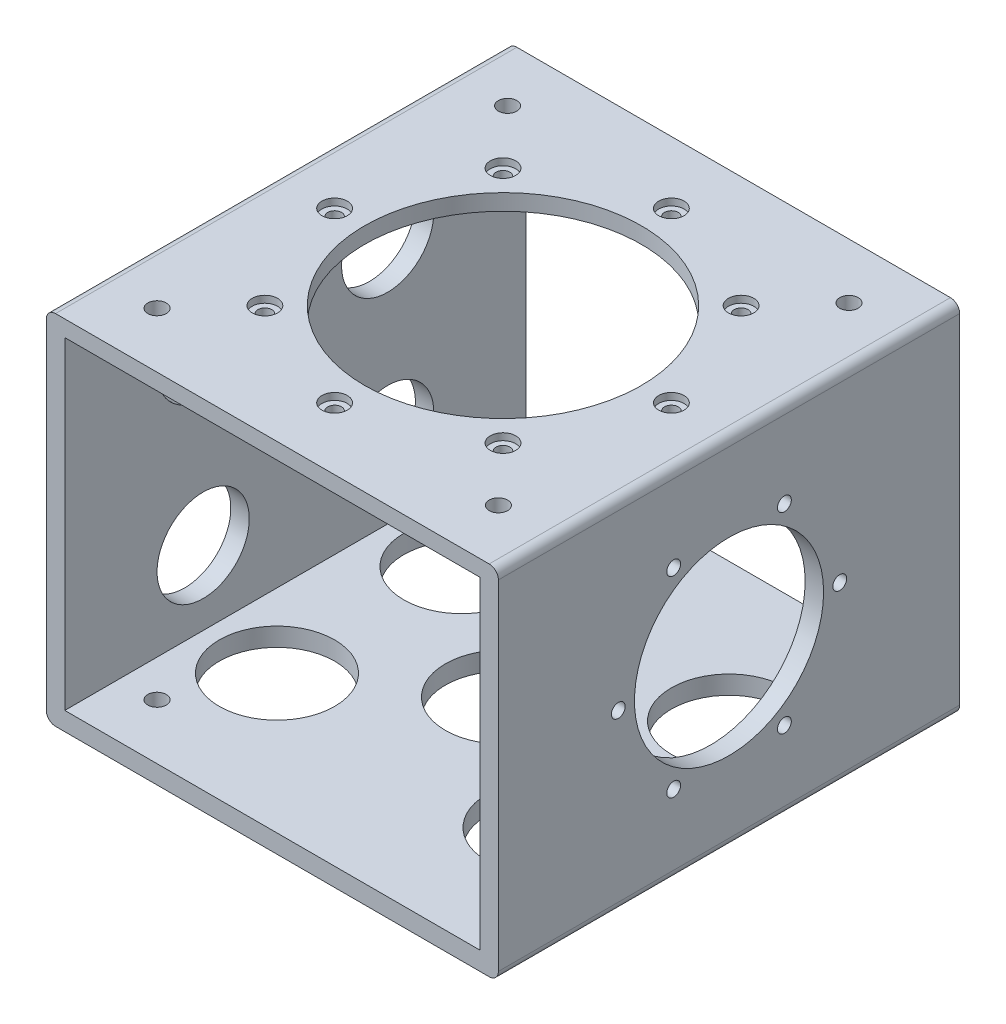
SolidWorks part; units mm, degrees
ref_plane "前视基准面" through (0, 0, 0) normal (0, 0, 1) x (1, 0, 0)
ref_plane "上视基准面" through (0, 0, 0) normal (0, 1, 0) x (1, 0, 0)
ref_plane "右视基准面" through (0, 0, 0) normal (1, 0, 0) x (0, 0, -1)
sketch "草图1" plane through (0, 0, 0) normal (0, 1, 0) x (1, 0, 0)
  line L1 (-45, 40) -> (45, 40)
  line L2 (-45, 40) -> (-45, -40)
  line L3 (-45, -40) -> (45, -40)
  line L4 (45, 40) -> (45, -40)
  line L5 (-45, 40) -> (45, -40) construction
  line L6 (-45, -40) -> (45, 40) construction
  circle A0 centre (0, 0) radius 30
  point P0 (0, 0)
  dimension "D3" = 60
  dimension "D1" = 80
  dimension "D2" = 90
extrude "凸台-拉伸1" add sketch "草图1" along normal blind 4
sketch "草图2" plane through (0, 4, 0) normal (0, 1, 0) x (1, 0, 0)
  circle A0 centre (0, 0) radius 36.5 construction
  circle A1 centre (0, 36.5) radius 1.5
  circle A2 centre (25.8094, 25.8094) radius 1.5
  circle A3 centre (36.5, 0) radius 1.5
  circle A4 centre (25.8094, -25.8094) radius 1.5
  circle A5 centre (0, -36.5) radius 1.5
  circle A6 centre (-25.8094, -25.8094) radius 1.5
  circle A7 centre (-36.5, 0) radius 1.5
  circle A8 centre (-25.8094, 25.8094) radius 1.5
  point P22 (0, 0)
  dimension "D1" = 73
  dimension "D2" = 3
  dimension "D3" = 8
extrude "切除-拉伸1" cut sketch "草图2" against normal blind 4
sketch "草图3" plane through (45, 0, 0) normal (1, 0, 0) x (0, 0, -1)
  line L1 (-40, 4) -> (40, 4)
  line L2 (-40, 4) -> (-40, -76)
  line L3 (-40, -76) -> (40, -76)
  line L4 (40, 4) -> (40, -76)
  dimension "D1" = 80
extrude "凸台-拉伸2" add sketch "草图3" along normal blind 4
sketch "草图4" plane through (-45, 0, 0) normal (-1, 0, 0) x (0, 0, 1)
  line L4 (40, -76) -> (40, 4)
  line L5 (-40, -76) -> (40, -76)
  line L6 (-40, 4) -> (-40, -76)
  line L7 (40, 4) -> (-40, 4)
  line L8 (40, -76) -> (40, 4)
  line L9 (-40, -76) -> (40, -76)
  line L10 (-40, 4) -> (-40, -76)
  line L11 (40, 4) -> (-40, 4)
  dimension "D1" = 0
extrude "凸台-拉伸3" add sketch "草图4" along normal blind 4
sketch "草图5" plane through (49, 0, 0) normal (1, 0, 0) x (0, 0, -1)
  line L0 (-40, -76) -> (40, -76) construction
  circle A0 centre (0, -36) radius 40 construction
  circle A1 centre (0, -36) radius 24 construction
  circle A2 centre (-24, -36) radius 1.5
  circle A3 centre (-12, -15.2154) radius 1.5
  circle A4 centre (12, -15.2154) radius 1.5
  circle A5 centre (24, -36) radius 1.5
  circle A6 centre (12, -56.7846) radius 1.5
  circle A7 centre (-12, -56.7846) radius 1.5
  point P20 (0, -36)
  dimension "D2" = 80
  dimension "D3" = 48
  dimension "D4" = 3
  dimension "D1" = 40
  dimension "D5" = 6
extrude "切除-拉伸2" cut sketch "草图5" against normal blind 4
sketch "草图6" plane through (49, 0, 0) normal (1, 0, 0) x (0, 0, -1)
  line L0 (-40, -76) -> (40, -76) construction
  circle A0 centre (0, -36) radius 20.5
  dimension "D2" = 41
  dimension "D1" = 40
extrude "切除-拉伸3" cut sketch "草图6" against normal blind 4
sketch "草图8" plane through (0, -76, 0) normal (0, -1, 0) x (1, 0, 0)
  line L1 (-49, 40) -> (49, 40)
  line L2 (-49, 40) -> (-49, -40)
  line L3 (-49, -40) -> (49, -40)
  line L4 (49, 40) -> (49, -40)
extrude "凸台-拉伸4" add sketch "草图8" against normal blind 4
sketch "草图9" plane through (-49, 0, 0) normal (-1, 0, 0) x (0, 0, 1)
  line L0 (0, 0) -> (0, -70.3657) construction
  line L1 (-46.4501, -36) -> (45.1919, -36) construction
  circle A0 centre (0, -36) radius 8
  dimension "D1" = 16
extrude "切除-拉伸5" cut sketch "草图9" against normal blind 4
sketch "草图10" plane through (0, 4, 0) normal (0, 1, 0) x (1, 0, 0)
  circle A0 centre (-25.8094, 25.8094) radius 2.75
  circle A1 centre (0, 36.5) radius 2.75
  circle A2 centre (25.8094, 25.8094) radius 2.75
  circle A3 centre (36.5, 0) radius 2.75
  circle A4 centre (25.8094, -25.8094) radius 2.75
  circle A5 centre (0, -36.5) radius 2.75
  circle A6 centre (-25.8094, -25.8094) radius 2.75
  circle A7 centre (-36.5, 0) radius 2.75
  point P20 (0, 0)
  dimension "D1" = 5.5
  dimension "D2" = 8
extrude "切除-拉伸6" cut sketch "草图10" against normal blind 2
sketch "草图11" plane through (0, -76, 0) normal (0, -1, 0) x (1, 0, 0)
  line L1 (-52.2176, 44.2603) -> (53.8702, 44.2603)
  line L2 (-52.2176, 44.2603) -> (-52.2176, -42.4352)
  line L3 (-52.2176, -42.4352) -> (53.8702, -42.4352)
  line L4 (53.8702, 44.2603) -> (53.8702, -42.4352)
extrude "切除-拉伸7" cut sketch "草图11" against normal blind 2
sketch "草图12" plane through (0, -72, 0) normal (0, 1, 0) x (1, 0, 0)
  line L4 (-45, -40) -> (45, -40)
  line L5 (45, -40) -> (45, 40)
  line L6 (45, 40) -> (-45, 40)
  line L7 (-45, 40) -> (-45, -40)
  line L8 (-45, -40) -> (45, -40)
  line L9 (45, -40) -> (45, 40)
  line L10 (45, 40) -> (-45, 40)
  line L11 (-45, 40) -> (-45, -40)
  dimension "D1" = 0
extrude "凸台-拉伸5" add sketch "草图12" along normal blind 2
sketch "草图13" plane through (0, 4, 0) normal (0, 1, 0) x (1, 0, 0)
  line L1 (-60.0477, 50.6634) -> (55.7544, 50.6634)
  line L2 (-60.0477, 50.6634) -> (-60.0477, -44.4127)
  line L3 (-60.0477, -44.4127) -> (55.7544, -44.4127)
  line L4 (55.7544, 50.6634) -> (55.7544, -44.4127)
extrude "切除-拉伸8" cut sketch "草图13" against normal blind 0.5
sketch "草图14" plane through (0, -74, 0) normal (0, -1, 0) x (1, 0, 0)
  line L0 (-49, -40) -> (-49, 40) construction
  line L1 (49, 40) -> (-49, 40) construction
  line L2 (49, 40) -> (49, -40) construction
  line L3 (-49, -40) -> (49, -40) construction
  circle A0 centre (-29, 20) radius 12.5
  circle A1 centre (29, 20) radius 12.5
  circle A2 centre (0, 0) radius 12.5
  circle A3 centre (-29, -20) radius 12.5
  circle A4 centre (29, -20) radius 12.5
  point P18 (0, -40)
  dimension "D1" = 25
  dimension "D2" = 25
  dimension "D3" = 25
  dimension "D4" = 25
  dimension "D11" = 20
  dimension "D13" = 25
  dimension "D5" = 20
  dimension "D6" = 20
  dimension "D7" = 20
  dimension "D8" = 20
  dimension "D9" = 20
  dimension "D10" = 20
  dimension "D12" = 20
  dimension "D14" = 40
  dimension "D15" = 49
extrude "切除-拉伸9" cut sketch "草图14" against normal up to surface (4 mm away) up to face at (0, -70, 0)
fillet "圆角1" radius 2 4 edges at (-49, -74, 0) (-49, 3.5, 0) (49, 3.5, 0) (49, -74, 0)
sketch "草图15" plane through (-49, 0, 0) normal (-1, 0, 0) x (0, 0, 1)
  line L0 (-40, 1.5) -> (-40, -72) construction
  line L1 (-40, 3.5) -> (40, 3.5) construction
  line L2 (40, -72) -> (40, 1.5) construction
  line L3 (40, -74) -> (-40, -74) construction
  circle A0 centre (-20, -16.5) radius 10
  circle A1 centre (20, -16.5) radius 10
  circle A2 centre (20, -54) radius 10
  circle A3 centre (-20, -54) radius 10
  dimension "D1" = 20
  dimension "D6" = 20
  dimension "D7" = 20
  dimension "D10" = 20
  dimension "D2" = 20
  dimension "D3" = 20
  dimension "D4" = 20
  dimension "D5" = 20
  dimension "D8" = 20
  dimension "D9" = 20
  dimension "D11" = 20
  dimension "D12" = 20
extrude "切除-拉伸10" cut sketch "草图15" against normal up to next
sketch "草图16" plane through (0, 0, -40) normal (0, 0, -1) x (-1, 0, 0)
  line L0 (-45, -70) -> (45, -70) construction
  line L1 (45, 0) -> (45, -70) construction
  line L2 (-45, 0) -> (45, 0) construction
  line L3 (-45, -70) -> (-45, 0) construction
  line L4 (-47, -74) -> (47, -74)
  line L5 (49, -72) -> (49, 1.5)
  line L6 (47, 3.5) -> (-47, 3.5)
  line L7 (-49, 1.5) -> (-49, -72)
  line L8 (-47, -74) -> (47, -74)
  line L9 (49, -72) -> (49, 1.5)
  line L10 (47, 3.5) -> (-47, 3.5)
  line L11 (-49, 1.5) -> (-49, -72)
  line L12 (-45, -70) -> (45, -70)
  line L13 (45, 0) -> (45, -70)
  line L14 (-45, 0) -> (45, 0)
  line L15 (-45, -70) -> (-45, 0)
  arc A4 (47, -74) -> (49, -72) centre (47, -72) ccw
  arc A5 (49, 1.5) -> (47, 3.5) centre (47, 1.5) ccw
  arc A6 (-47, 3.5) -> (-49, 1.5) centre (-47, 1.5) ccw
  arc A7 (-49, -72) -> (-47, -74) centre (-47, -72) ccw
  arc A8 (47, -74) -> (49, -72) centre (47, -72) ccw
  arc A9 (49, 1.5) -> (47, 3.5) centre (47, 1.5) ccw
  arc A10 (-47, 3.5) -> (-49, 1.5) centre (-47, 1.5) ccw
  arc A11 (-49, -72) -> (-47, -74) centre (-47, -72) ccw
  dimension "D1" = 0
extrude "凸台-拉伸6" add sketch "草图16" along normal blind 10
sketch "草图17" plane through (0, 0, 40) normal (0, 0, 1) x (1, 0, 0)
  line L0 (-45, -70) -> (45, -70) construction
  line L1 (45, 0) -> (45, -70) construction
  line L2 (-45, 0) -> (45, 0) construction
  line L3 (-45, -70) -> (-45, 0) construction
  line L4 (-49, 1.5) -> (-49, -72)
  line L5 (-47, -74) -> (47, -74)
  line L6 (49, -72) -> (49, 1.5)
  line L7 (47, 3.5) -> (-47, 3.5)
  line L8 (-49, 1.5) -> (-49, -72)
  line L9 (-47, -74) -> (47, -74)
  line L10 (49, -72) -> (49, 1.5)
  line L11 (47, 3.5) -> (-47, 3.5)
  line L12 (-45, -70) -> (45, -70)
  line L13 (45, 0) -> (45, -70)
  line L14 (-45, 0) -> (45, 0)
  line L15 (-45, -70) -> (-45, 0)
  arc A4 (-49, -72) -> (-47, -74) centre (-47, -72) ccw
  arc A5 (47, -74) -> (49, -72) centre (47, -72) ccw
  arc A6 (49, 1.5) -> (47, 3.5) centre (47, 1.5) ccw
  arc A7 (-47, 3.5) -> (-49, 1.5) centre (-47, 1.5) ccw
  arc A8 (-49, -72) -> (-47, -74) centre (-47, -72) ccw
  arc A9 (47, -74) -> (49, -72) centre (47, -72) ccw
  arc A10 (49, 1.5) -> (47, 3.5) centre (47, 1.5) ccw
  arc A11 (-47, 3.5) -> (-49, 1.5) centre (-47, 1.5) ccw
  dimension "D1" = 0
extrude "凸台-拉伸7" add sketch "草图17" along normal blind 10
sketch "草图19" plane through (0, -74, 0) normal (0, -1, 0) x (1, 0, 0)
  line L0 (-47, 50) -> (47, 50) construction
  line L1 (-49, -50) -> (-49, 50) construction
  line L2 (49, 50) -> (49, -50) construction
  line L3 (-57.0828, 0) -> (55.3962, 0) construction
  circle A0 centre (37, -38) radius 2
  circle A1 centre (-37, 38) radius 2
  circle A2 centre (37, 38) radius 2
  circle A3 centre (-37, -38) radius 2
  dimension "D2" = 4
  dimension "D3" = 4
  dimension "D4" = 12
  dimension "D5" = 12
  dimension "D6" = 12
  dimension "D7" = 12
extrude "切除-拉伸12" cut sketch "草图19" against normal through all
sketch "草图20" plane through (-49, 0, 0) normal (-1, 0, 0) x (0, 0, 1)
  circle A0 centre (0, -36) radius 8
  circle A1 centre (0, -36) radius 7.5
  dimension "D1" = 15
extrude "凸台-拉伸8" add sketch "草图20" against normal up to surface (4 mm away) up to face at (-45, -16.5, 30)
